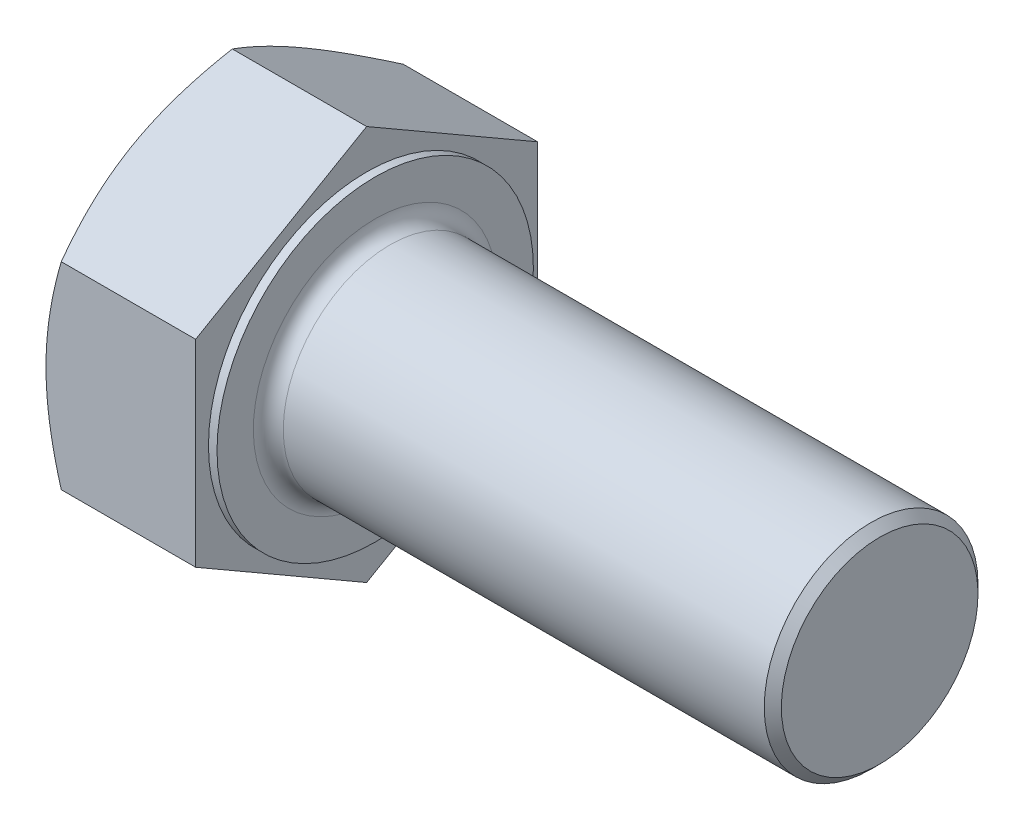
SolidWorks part; units mm, degrees
material "Acciaio al carbonio semplice"
ref_plane "Piano frontale" through (0, 0, 0) normal (0, 0, 1) x (1, 0, 0)
ref_plane "Piano superiore" through (0, 0, 0) normal (0, 1, 0) x (1, 0, 0)
ref_plane "Piano destro" through (0, 0, 0) normal (1, 0, 0) x (0, 0, -1)
sketch "Schizzo1" plane through (0, 0, 0) normal (0, 0, 1) x (1, 0, 0)
  line L0 (0.2, 2.5) -> (12, 2.5)
  line L1 (12, 2.5) -> (12, 0)
  line L2 (12, 0) -> (0, 0)
  line L3 (0, 0) -> (0, 3.7)
  line L4 (0, 3.7) -> (0.2, 3.7)
  line L7 (0.2, 3.7) -> (0.2, 2.5)
  dimension "D1" = 12
  dimension "D2" = 0.2
  dimension "D3" = 2.5
  dimension "D4" = 3.7
revolve "Rivoluzione1" add sketch "Schizzo1" angle 360 about L2
cosmetic thread "Filettatura cosmetica4" parameters "D2"=4.11
sketch "Schizzo2" plane through (0, 0, 0) normal (-1, 0, 0) x (0, 0, 1)
  line L1 (0, -4.6188) -> (4, -2.3094)
  line L2 (4, -2.3094) -> (4, 2.3094)
  line L3 (4, 2.3094) -> (0, 4.6188)
  line L4 (0, 4.6188) -> (-4, 2.3094)
  line L5 (-4, 2.3094) -> (-4, -2.3094)
  line L6 (-4, -2.3094) -> (0, -4.6188)
  circle A0 centre (0, 0) radius 4 construction
  dimension "D1" = 8
extrude "Estrusione-Estrusione1" add sketch "Schizzo2" along normal blind 3.5 contours L4 L5 L6 L1 L2 L3
sketch "Schizzo3" plane through (0, 0, 0) normal (0, 0, 1) x (1, 0, 0)
  line L0 (-3.5, 4) -> (-3.1427, 4.6188)
  line L1 (-3.5, 4.6188) -> (0, 4.6188) construction
  line L2 (-3.5, 2.3094) -> (-3.5, 4.6188) construction
  line L3 (-3.5, 4.6188) -> (0, 4.6188) construction
  line L4 (-3.5, 2.3094) -> (-3.5, 4.6188) construction
  line L5 (-3.5, -2.3094) -> (-3.5, 2.3094) construction
  line L6 (-3.5, 4) -> (-3.5, 4.6188)
  line L7 (-3.5, 4.6188) -> (-3.1427, 4.6188)
  point P6 (-3.5, 0)
  dimension "D1" = 30
  dimension "D2" = 4
ref_axis "Assi1" through (0.2, 0, 0) along (1, 0, 0)
revolve "Taglia-Rivoluzione3" cut sketch "Schizzo3" angle 360 about axis through (0.2, 0, 0) along (1, 0, 0)
chamfer "Smusso1" distance 0.2 angle 45 1 edges at (12, 2.5, 0)
fillet "Raccordo1" radius 0.35 1 edges at (0.2, 2.5, 0)
